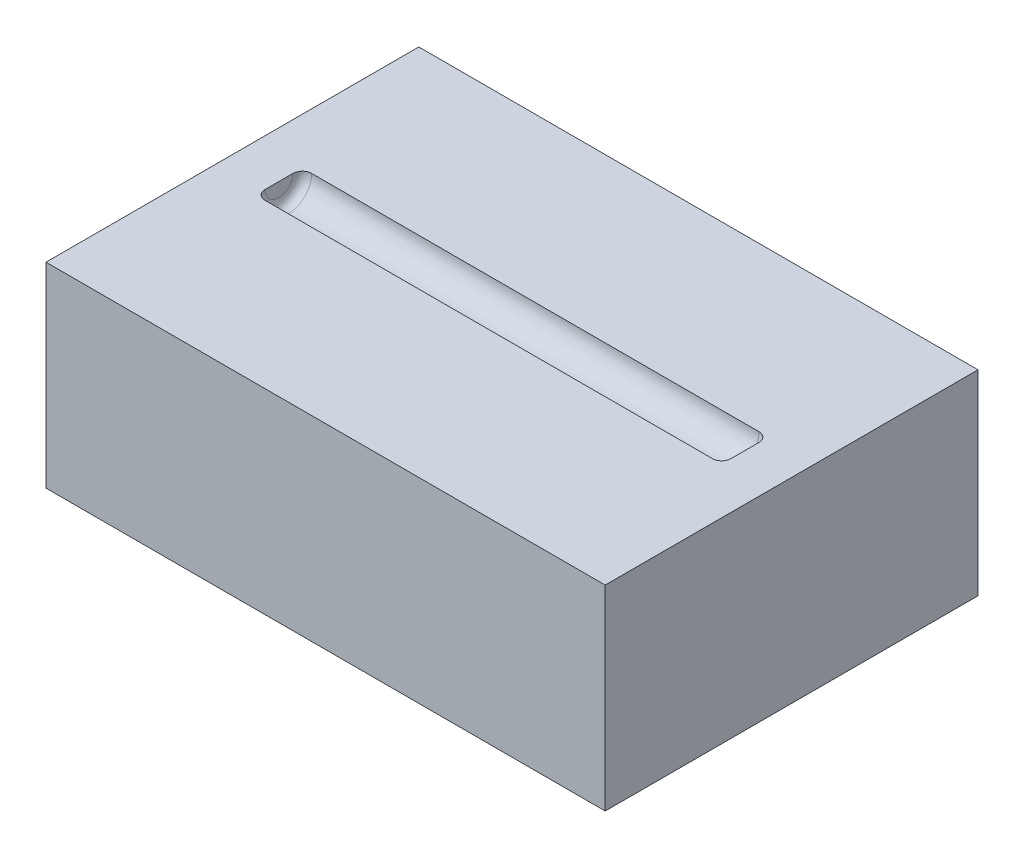
SolidWorks part; units mm, degrees
ref_plane "Front Plane" through (0, 0, 0) normal (0, 0, 1) x (1, 0, 0)
ref_plane "Top Plane" through (0, 0, 0) normal (0, 1, 0) x (1, 0, 0)
ref_plane "Right Plane" through (0, 0, 0) normal (1, 0, 0) x (0, 0, -1)
sketch "Sketch1" plane through (0, 0, 0) normal (0, 1, 0) x (1, 0, 0)
  line L1 (-76.2, -50.8) -> (76.2, -50.8)
  line L2 (-76.2, -50.8) -> (-76.2, 50.8)
  line L3 (-76.2, 50.8) -> (76.2, 50.8)
  line L4 (76.2, -50.8) -> (76.2, 50.8)
  line L5 (-76.2, -50.8) -> (76.2, 50.8) construction
  line L6 (-76.2, 50.8) -> (76.2, -50.8) construction
  point P0 (0, 0)
  dimension "D1" = 152.4
  dimension "D2" = 101.6
extrude "Boss-Extrude1" add sketch "Sketch1" against normal blind 53.34
sketch "Sketch2" plane through (76.2, 0, 0) normal (1, 0, 0) x (0, 0, -1)
  line L0 (0, -1000) -> (0, 49000) construction
  line L1 (-50.8, 0) -> (50.8, 0) construction
  circle A0 centre (0, 0) radius 6.35
  point P5 (0, 0)
  dimension "D1" = 12.7
extrude "Cut-Extrude1" cut sketch "Sketch2" against normal offset from surface (127 mm away) 12.7 from offset 12.7 up to face at (-76.2, -26.67, 0) offset against normal yes
fillet "Fillet2" radius 2.54 2 edges at (63.5, -6.35, 0) (-63.5, -6.35, 0)
